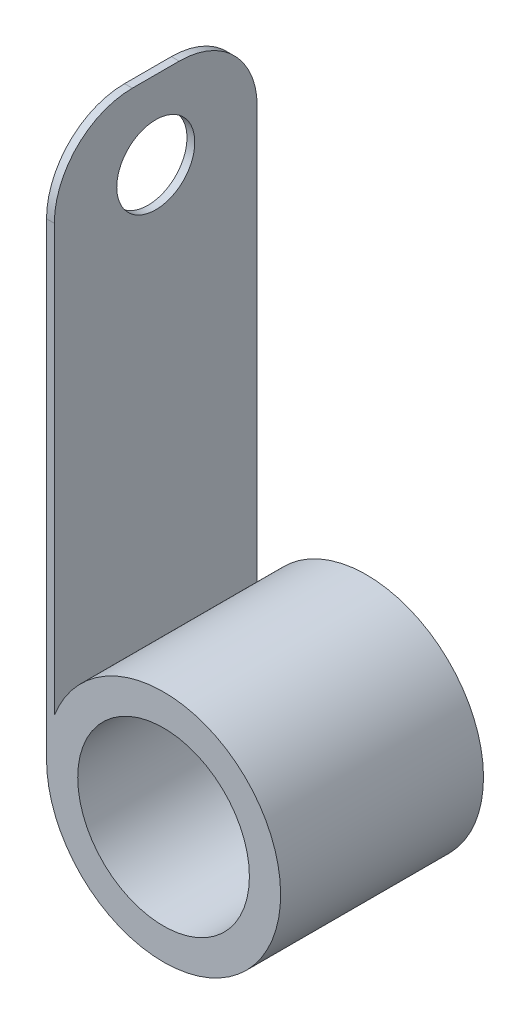
SolidWorks part; units mm, degrees
ref_plane "Plano frontal" through (0, 0, 0) normal (0, 0, 1) x (1, 0, 0)
ref_plane "Plano superior" through (0, 0, 0) normal (0, 1, 0) x (1, 0, 0)
ref_plane "Plano direito" through (0, 0, 0) normal (1, 0, 0) x (0, 0, -1)
sketch "Esboço1" plane through (0, 0, 0) normal (0, 0, 1) x (1, 0, 0)
  circle A0 centre (0, 0) radius 7.5
  circle A1 centre (0, 0) radius 5.5
  point P4 (5.5, 0)
  point P5 (7.5, 0)
  dimension "D1" = 15
  dimension "D2" = 2
extrude "Ressalto-extrusão1" add sketch "Esboço1" along normal blind 13
sketch "Esboço2" plane through (0, 0, 0) normal (0, 1, 0) x (1, 0, 0)
  line L0 (-7.5, -13) -> (7.5, -13) construction
  line L1 (-7.5, 0) -> (-7, 0)
  line L2 (-7.5, 0) -> (-7.5, -13)
  line L3 (-7.5, -13) -> (-7, -13)
  line L4 (-7, 0) -> (-7, -13)
  dimension "D1" = 0.5
extrude "Ressalto-extrusão2" add sketch "Esboço2" along normal blind 35
sketch "Esboço3" plane through (-7.5, 0, 0) normal (-1, 0, 0) x (0, 0, 1)
  line L0 (0, 35) -> (13, 35) construction
  circle A0 centre (6.5, 30) radius 2.5
  point P2 (6.5, 35)
  point P3 (0, 0)
  dimension "D1" = 5
  dimension "D2" = 5
extrude "Corte-extrusão1" cut sketch "Esboço3" against normal blind 20
fillet "Filete1" radius 5 2 edges at (-7.25, 35, 0) (-7.25, 35, 13)
